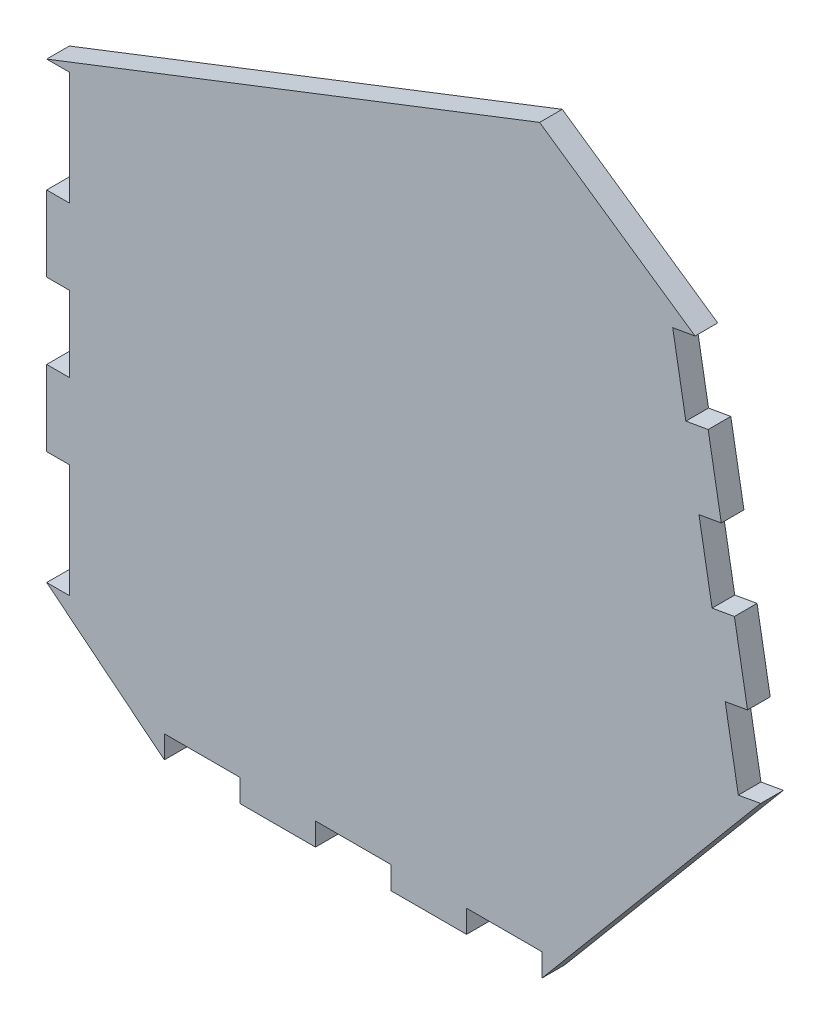
SolidWorks part; units mm, degrees
ref_plane "Plan de face" through (0, 0, 0) normal (0, 0, 1) x (1, 0, 0)
ref_plane "Plan de dessus" through (0, 0, 0) normal (0, 1, 0) x (1, 0, 0)
ref_plane "Plan de droite" through (0, 0, 0) normal (1, 0, 0) x (0, 0, -1)
sketch "Sketch1" plane through (0, 0, 0) normal (0, 0, 1) x (1, 0, 0)
  line L0 (-31.8099, -18.296) -> (-16.2349, -30.8427)
  line L1 (33.7651, -30.8427) -> (-16.2349, -30.8427)
  line L2 (33.7651, -30.8427) -> (62.6905, 3.6293)
  line L3 (62.6905, 3.6293) -> (54.0081, 52.8697)
  line L4 (54.0081, 52.8697) -> (33.4325, 67.0699)
  line L5 (33.4325, 67.0699) -> (-31.8099, 41.704)
  line L6 (-31.8099, 41.704) -> (-31.8099, -18.296)
  line L7 (-31.8099, 41.704) -> (-31.8099, 26.704)
  line L8 (-31.8099, 41.704) -> (-28.8099, 41.704)
  line L9 (-31.8099, 26.704) -> (-28.8099, 26.704)
  line L10 (-28.8099, 41.704) -> (-28.8099, 26.704)
  line L11 (-31.8099, 16.704) -> (-31.8099, 6.704)
  line L12 (-31.8099, 16.704) -> (-28.8099, 16.704)
  line L13 (-31.8099, 6.704) -> (-28.8099, 6.704)
  line L14 (-28.8099, 16.704) -> (-28.8099, 6.704)
  line L15 (-31.8099, -18.296) -> (-31.8099, -3.296)
  line L16 (-31.8099, -18.296) -> (-28.8099, -18.296)
  line L17 (-31.8099, -3.296) -> (-28.8099, -3.296)
  line L18 (-28.8099, -18.296) -> (-28.8099, -3.296)
  line L19 (-16.2349, -30.8427) -> (-6.2349, -30.8427)
  line L20 (-16.2349, -30.8427) -> (-16.2349, -27.8427)
  line L21 (-6.2349, -30.8427) -> (-6.2349, -27.8427)
  line L22 (-16.2349, -27.8427) -> (-6.2349, -27.8427)
  line L23 (3.7651, -30.8427) -> (13.7651, -30.8427)
  line L24 (3.7651, -30.8427) -> (3.7651, -27.8427)
  line L25 (13.7651, -30.8427) -> (13.7651, -27.8427)
  line L26 (3.7651, -27.8427) -> (13.7651, -27.8427)
  line L27 (33.7651, -30.8427) -> (23.7651, -30.8427)
  line L28 (33.7651, -30.8427) -> (33.7651, -27.8427)
  line L29 (23.7651, -30.8427) -> (23.7651, -27.8427)
  line L30 (33.7651, -27.8427) -> (23.7651, -27.8427)
  line L31 (54.0081, 52.8697) -> (55.7446, 43.0216)
  line L32 (54.0081, 52.8697) -> (51.0537, 52.3488)
  line L33 (55.7446, 43.0216) -> (52.7902, 42.5007)
  line L34 (51.0537, 52.3488) -> (52.7902, 42.5007)
  line L35 (57.4811, 33.1736) -> (59.2175, 23.3255)
  line L36 (57.4811, 33.1736) -> (54.5266, 32.6526)
  line L37 (59.2175, 23.3255) -> (56.2631, 22.8045)
  line L38 (54.5266, 32.6526) -> (56.2631, 22.8045)
  line L39 (62.6905, 3.6293) -> (60.954, 13.4774)
  line L40 (62.6905, 3.6293) -> (59.7361, 3.1084)
  line L41 (60.954, 13.4774) -> (57.9996, 12.9565)
  line L42 (59.7361, 3.1084) -> (57.9996, 12.9565)
  dimension "D1" = 50
  dimension "D2" = 60
  dimension "D3" = 50
  dimension "D4" = 70
  dimension "D5" = 25
  dimension "D6" = 45
  dimension "D7" = 20
  dimension "D8" = 230
  dimension "D9" = 280
  dimension "D10" = 3
  dimension "D11" = 3
  dimension "D12" = 3
  dimension "D13" = 15
  dimension "D14" = 10
  dimension "D15" = 15
  dimension "D16" = 10
  dimension "D17" = 10
  dimension "D18" = 3
  dimension "D19" = 3
  dimension "D20" = 3
  dimension "D21" = 10
  dimension "D22" = 10
  dimension "D23" = 10
  dimension "D24" = 10
  dimension "D25" = 10
  dimension "D26" = 3
  dimension "D27" = 3
  dimension "D28" = 3
  dimension "D29" = 10
  dimension "D30" = 10
  dimension "D31" = 10
  dimension "D32" = 10
  dimension "D33" = 10
extrude "Boss-Extrude2" add sketch "Sketch1" along normal blind 3 contours L40 L42 L41 L3 L37 L38 L36 L33 L34 L32 L4 L5 L8 L10 L9 L6 L12 L14 L13 L17 L18 L16 L0 L20 L22 L21 L1 L24 L26 L25 L29 L30 L28 L2
